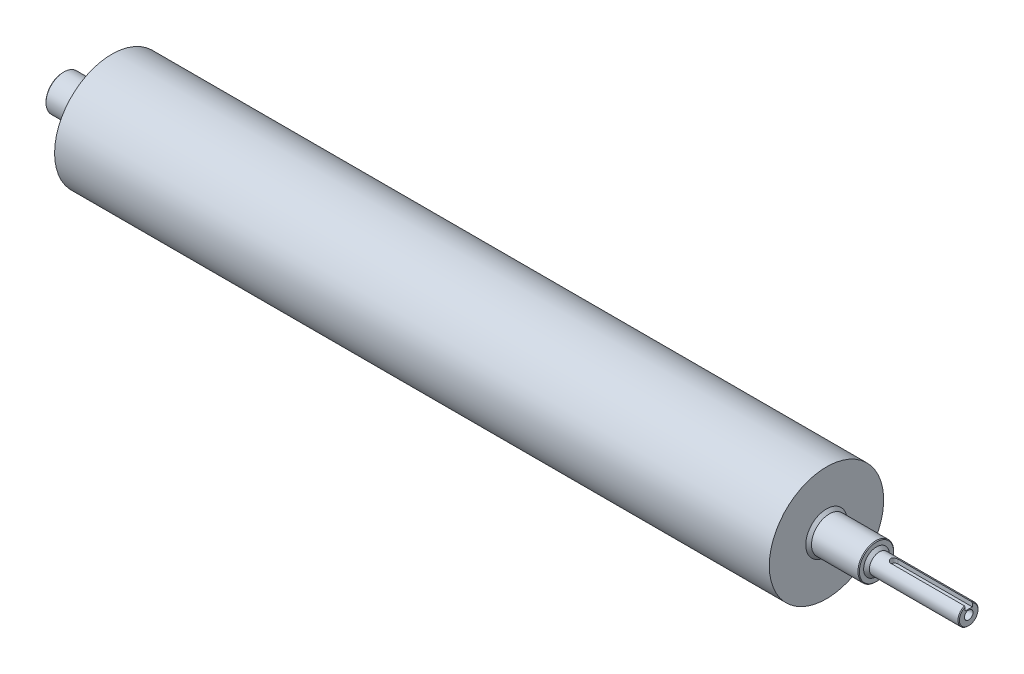
SolidWorks part; units mm, degrees
material "3.3549 (EN-AW 5182)"
ref_plane "Piano frontale" through (0, 0, 0) normal (0, 0, 1) x (1, 0, 0)
ref_plane "Piano superiore" through (0, 0, 0) normal (0, 1, 0) x (1, 0, 0)
ref_plane "Piano destro" through (0, 0, 0) normal (1, 0, 0) x (0, 0, -1)
sketch "Schizzo1" plane through (0, 0, 0) normal (1, 0, 0) x (0, 0, -1)
  circle A0 centre (0, 0) radius 12.5
  dimension "D1" = 25
extrude "Estrusione1" add sketch "Schizzo1" along normal blind 569
sketch "Schizzo2" plane through (569, 0, 0) normal (1, 0, 0) x (0, 0, -1)
  circle A0 centre (0, 0) radius 7
  dimension "D1" = 14
extrude "Estrusione2" add sketch "Schizzo2" along normal blind 64.5
sketch "Schizzo3" plane through (633.5, 0, 0) normal (1, 0, 0) x (0, 0, -1)
  circle A0 centre (0, 0) radius 3
  dimension "D1" = 6
extrude "Taglio-Estrusione1" cut sketch "Schizzo3" against normal blind 20
sketch "Schizzo4" plane through (0, 0, 0) normal (-1, 0, 0) x (0, 0, 1)
  circle A0 centre (0, 0) radius 3 construction
  circle A1 centre (0, 0) radius 3
extrude "Taglio-Estrusione2" cut sketch "Schizzo4" against normal blind 20
ref_plane "Piano1" through (34, 0, 0) normal (-1, 0, 0) x (0, 0, 1)
sketch "Schizzo5" plane through (34, 0, 0) normal (-1, 0, 0) x (0, 0, 1)
  circle A0 centre (0, 0) radius 40
  dimension "D1" = 80
extrude "Estrusione3" add sketch "Schizzo5" against normal blind 500
chamfer "Smusso1" distance 2 angle 45 3 edges at (569, 0, -7) (34, 0, 12.5) (534, 0, 12.5)
chamfer "Smusso2" distance 0.5 angle 45 3 edges at (0, 0, -12.5) (633.5, 0, -7) (569, 0, -12.5)
sketch "Schizzo7" plane through (633.5, 0, 0) normal (1, 0, 0) x (0, 0, -1)
  line L0 (0, 18.6278) -> (0, -19.9921) construction
  line L1 (-20.6218, 0) -> (21.5663, 0) construction
  line L4 (-2.5, 6.5383) -> (-2.5, 3.65)
  line L5 (-2.5, 3.65) -> (2.5, 3.65)
  line L6 (2.5, 6.5383) -> (2.5, 3.65)
  circle A1 centre (0, 0) radius 3.65 construction
  circle A2 centre (0, 0) radius 7 construction
  arc A3 (2.5, 6.5383) -> (-2.5, 6.5383) centre (0, 0) ccw
  dimension "D1" = 7.3
  dimension "D2" = 5
  dimension "D3" = 2.5
extrude "Taglio-Estrusione3" cut sketch "Schizzo7" against normal blind 52
sketch "Schizzo8" plane through (0, 3.65, 0) normal (0, 1, 0) x (1, 0, 0)
  line L0 (581.5, -2.5) -> (581.5, 2.5) construction
  line L1 (581.5, -2.5) -> (581.5, 2.5)
  arc A0 (581.5, 2.5) -> (581.5, -2.5) centre (581.5, 0) ccw
  dimension "D1" = 2.5
extrude "Taglio-Estrusione4" cut sketch "Schizzo8" along normal blind 10
